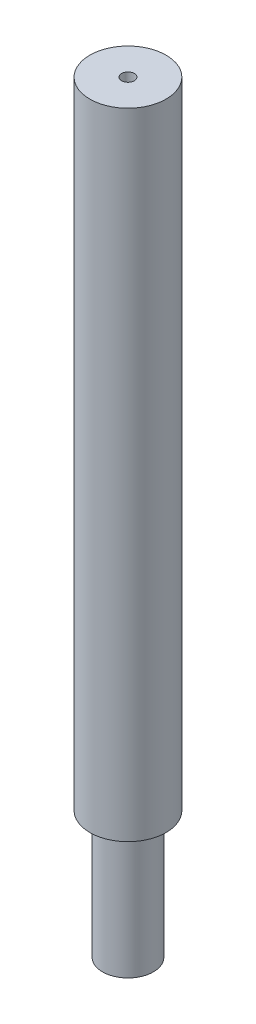
SolidWorks part; units mm, degrees
ref_plane "Front Plane" through (0, 0, 0) normal (0, 0, 1) x (1, 0, 0)
ref_plane "Top Plane" through (0, 0, 0) normal (0, 1, 0) x (1, 0, 0)
ref_plane "Right Plane" through (0, 0, 0) normal (1, 0, 0) x (0, 0, -1)
sketch "Sketch1" plane through (0, 0, 0) normal (0, 1, 0) x (1, 0, 0)
  circle A0 centre (0, 0) radius 2.54
  dimension "D1" = 5.08
extrude "Boss-Extrude1" add sketch "Sketch1" along normal blind 12.7
sketch "Sketch2" plane through (0, 12.7, 0) normal (0, 1, 0) x (1, 0, 0)
  circle A0 centre (0, 0) radius 3.81
  dimension "D1" = 7.62
extrude "Boss-Extrude2" add sketch "Sketch2" along normal blind 63.5
sketch "Sketch3" plane through (0, 76.2, 0) normal (0, 1, 0) x (1, 0, 0)
  circle A0 centre (0, 0) radius 0.635
  dimension "D1" = 1.27
extrude "Cut-Extrude1" cut sketch "Sketch3" against normal through all
